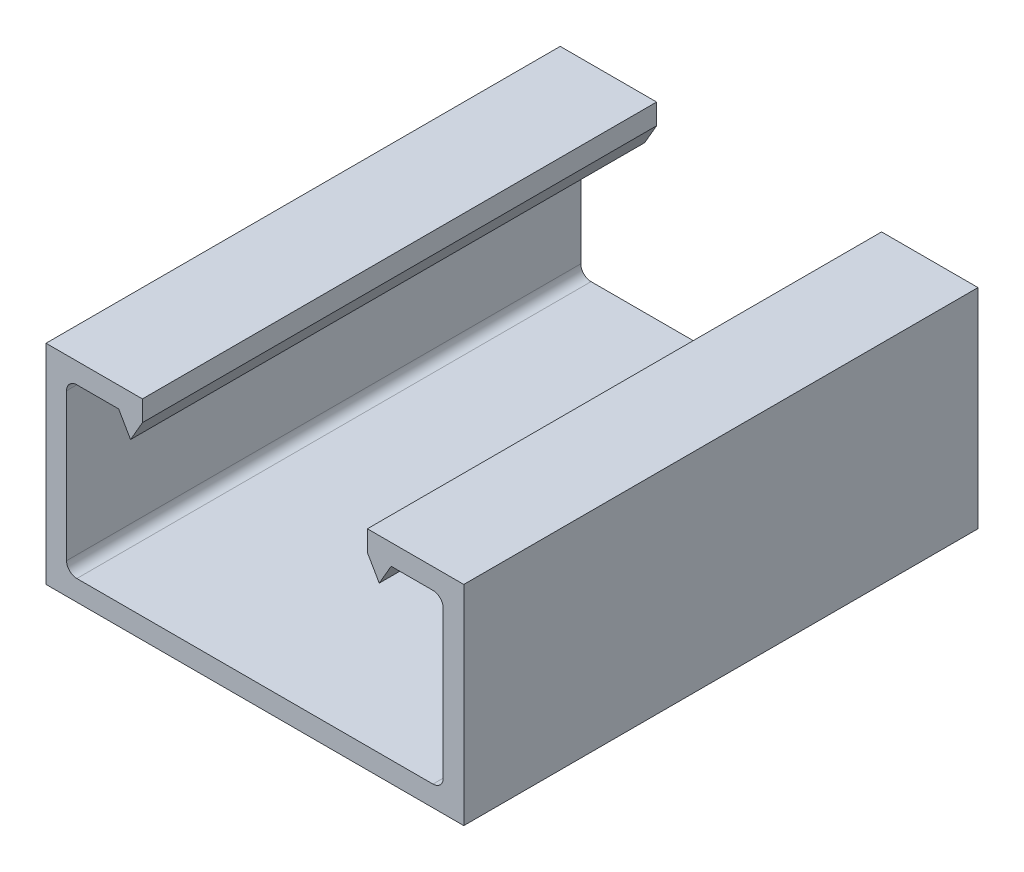
SolidWorks part; units mm, degrees
ref_plane "Plane1" through (0, 0, 0) normal (0, 0, 1) x (1, 0, 0)
ref_plane "Plane2" through (0, 0, 0) normal (0, 1, 0) x (1, 0, 0)
ref_plane "Plane3" through (0, 0, 0) normal (1, 0, 0) x (0, 0, -1)
sketch "Sketch1" plane through (0, 0, 0) normal (0, 0, 1) x (1, 0, 0)
  line L0 (-5.5563, 5.1594) -> (-10.3187, 5.1594)
  line L1 (-10.3187, 5.1594) -> (-10.3187, -5.1594)
  line L2 (-10.3187, -5.1594) -> (10.3188, -5.1594)
  line L3 (10.3188, -5.1594) -> (10.3187, 5.1594)
  line L4 (10.3187, 5.1594) -> (5.5562, 5.1594)
  line L5 (8.7948, 4.1434) -> (6.7294, 4.1434)
  line L6 (9.3028, -3.6354) -> (9.3027, 3.6354)
  line L7 (-8.7948, -4.1434) -> (8.7948, -4.1434)
  line L8 (-9.3028, 3.6354) -> (-9.3027, -3.6354)
  line L9 (-6.7294, 4.1434) -> (-8.7948, 4.1434)
  line L10 (6.7294, 4.1434) -> (6.1428, 3.1274)
  line L11 (6.1428, 3.1274) -> (5.5562, 4.1434)
  line L12 (5.5562, 4.1434) -> (5.5562, 5.1594)
  line L13 (-6.7294, 4.1434) -> (-6.1428, 3.1274)
  line L14 (-6.1428, 3.1274) -> (-5.5563, 4.1434)
  line L15 (-5.5563, 4.1434) -> (-5.5563, 5.1594)
  arc A0 (-9.3027, -3.6354) -> (-8.7948, -4.1434) centre (-8.7948, -3.6354) ccw
  arc A1 (-8.7948, 4.1434) -> (-9.3028, 3.6354) centre (-8.7948, 3.6354) ccw
  arc A2 (9.3027, 3.6354) -> (8.7948, 4.1434) centre (8.7948, 3.6354) ccw
  arc A3 (8.7948, -4.1434) -> (9.3028, -3.6354) centre (8.7948, -3.6354) ccw
  dimension "D5" = 0.508
  dimension "Width" = 20.6375
  dimension "Height" = 10.3187
  dimension "D8" = 10.3187
  dimension "D9" = 5.1594
  dimension "D10" = 11.1125
  dimension "edge" = 4.7625
  dimension "D13" = 0.5866
  dimension "D4" = 60
extrude "Base-Extrude" add sketch "Sketch1" along normal mid plane 25.4
equation "\"D8@Sketch1\" = \"Width@Sketch1\" / 2"
equation "\"D9@Sketch1\" = \"Height@Sketch1\" / 2"
equation "\"D10@Sketch1\" = \"Width@Sketch1\" - 2 * \"edge@Sketch1\""
equation "\"D5@Sketch1\" = \"gauge@Sketch1\" / 2"
equation "\"D13@Sketch1\" = \"gauge@Sketch1\" * .577350269"
